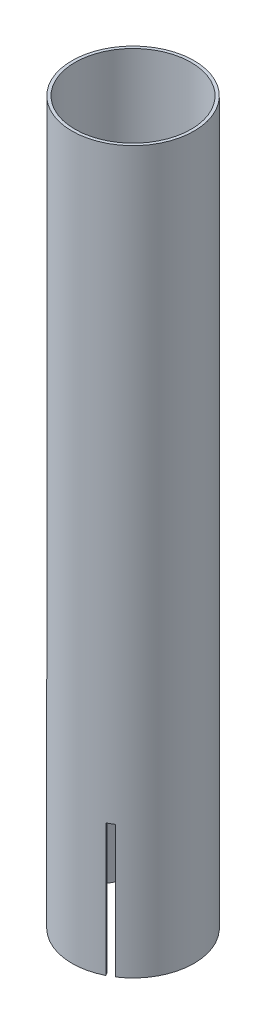
SolidWorks part; units mm, degrees
ref_plane "Front Plane" through (0, 0, 0) normal (0, 0, 1) x (1, 0, 0)
ref_plane "Top Plane" through (0, 0, 0) normal (0, 1, 0) x (1, 0, 0)
ref_plane "Right Plane" through (0, 0, 0) normal (1, 0, 0) x (0, 0, -1)
sketch "Sketch1" plane through (0, 0, 0) normal (0, 1, 0) x (1, 0, 0)
  circle A0 centre (0, 0) radius 25.4
  circle A1 centre (0, 0) radius 24.15
  dimension "D1" = 50.8
  dimension "D2" = 48.3
extrude "Boss-Extrude1" add sketch "Sketch1" along normal blind 300
sketch "Sketch2" plane through (0, 0, 0) normal (1, 0, 0) x (0, 0, -1)
  line L0 (-39.08, 0) -> (46.7898, 0) construction
  line L1 (0, 20.9368) -> (0, -10.5489) construction
  line L3 (-1.5, 55) -> (1.5, 55)
  line L4 (-1.5, 55) -> (-1.5, 0)
  line L5 (-1.5, 0) -> (1.5, 0)
  line L6 (1.5, 55) -> (1.5, 0)
  point P9 (0, 0)
  dimension "D1" = 55
  dimension "D2" = 3
extrude "Cut-Extrude1" cut sketch "Sketch2" against normal blind 35
pattern_circular "CirPattern1" count 3 over 360 about axis through (0, 0, 0) along (0, 1, 0) of "Cut-Extrude1"
